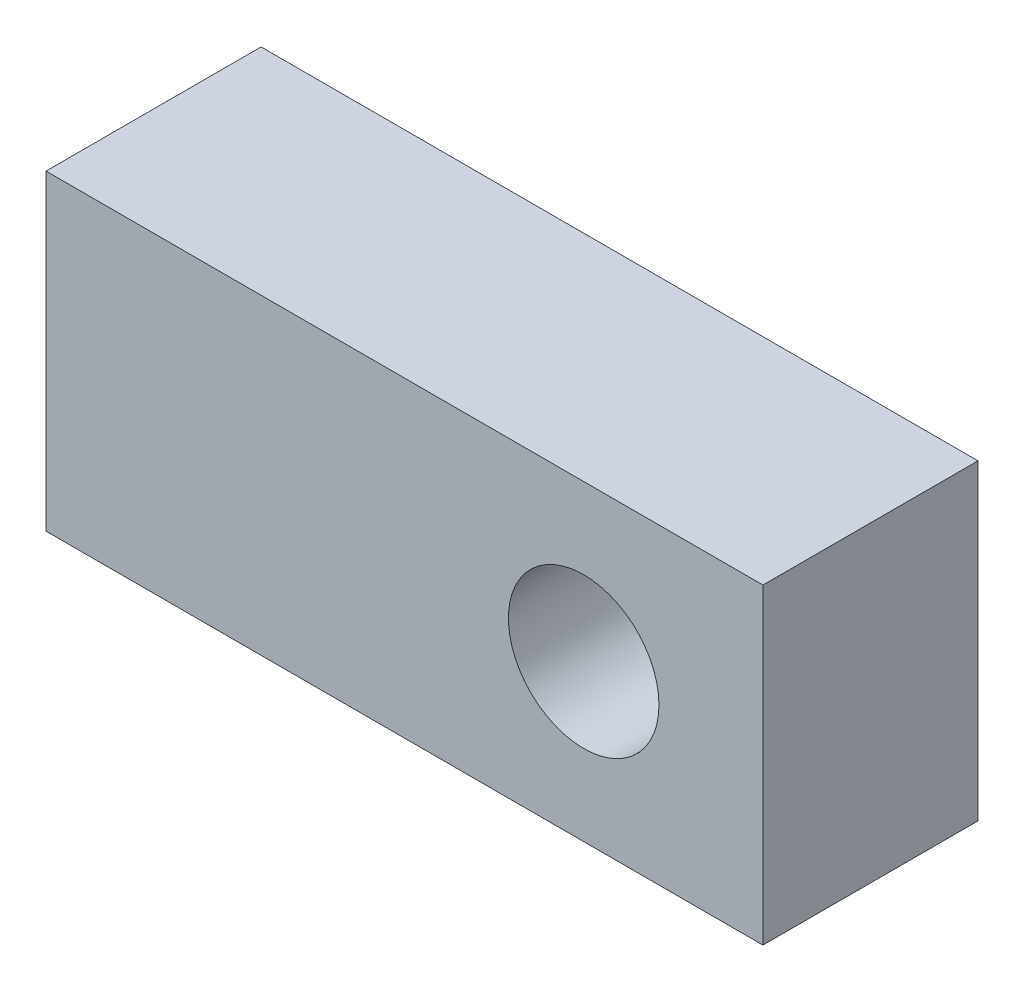
SolidWorks part; units mm, degrees
ref_plane "前视基准面" through (0, 0, 0) normal (0, 0, 1) x (1, 0, 0)
ref_plane "上视基准面" through (0, 0, 0) normal (0, 1, 0) x (1, 0, 0)
ref_plane "右视基准面" through (0, 0, 0) normal (1, 0, 0) x (0, 0, -1)
sketch "草图1" plane through (0, 0, 0) normal (0, 0, 1) x (1, 0, 0)
  line L1 (-10, -4.35) -> (10, -4.35)
  line L2 (-10, -4.35) -> (-10, 4.35)
  line L3 (-10, 4.35) -> (10, 4.35)
  line L4 (10, -4.35) -> (10, 4.35)
  line L5 (-10, -4.35) -> (10, 4.35) construction
  line L6 (-10, 4.35) -> (10, -4.35) construction
  circle A0 centre (5, 0) radius 2.1
  point P0 (0, 0)
  point P8 (0, 0)
  dimension "D3" = 5
  dimension "D4" = 4.2
  dimension "D1" = 8.7
  dimension "D2" = 20
extrude "凸台-拉伸1" add sketch "草图1" along normal mid plane 6
